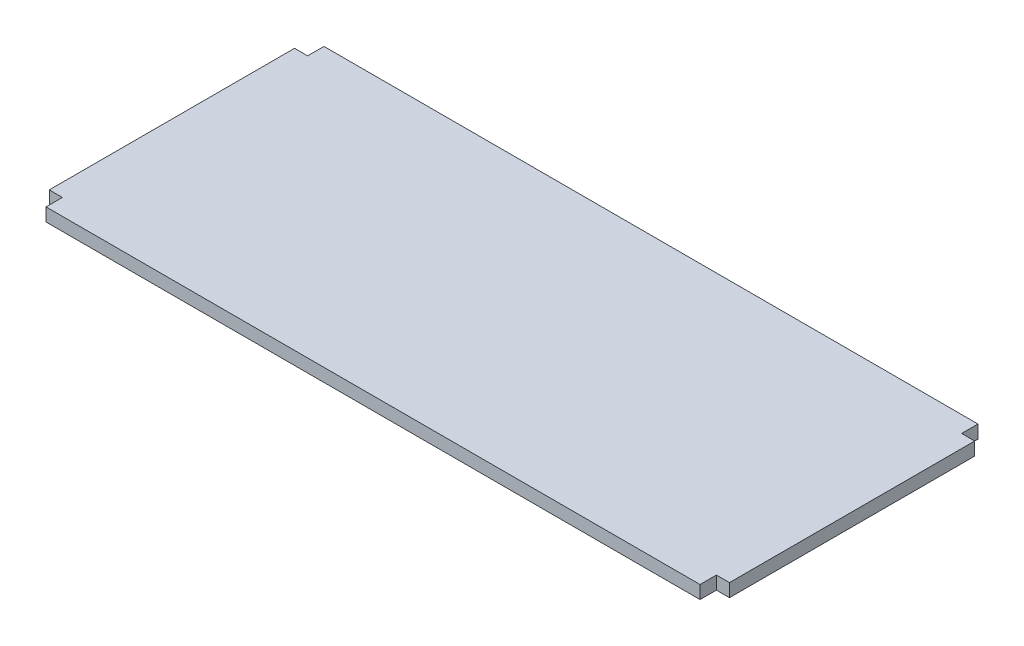
SolidWorks part; units mm, degrees
ref_plane "前视基准面" through (0, 0, 0) normal (0, 0, 1) x (1, 0, 0)
ref_plane "上视基准面" through (0, 0, 0) normal (0, 1, 0) x (1, 0, 0)
ref_plane "右视基准面" through (0, 0, 0) normal (1, 0, 0) x (0, 0, -1)
sketch "草图1" plane through (0, 0, 0) normal (0, 1, 0) x (1, 0, 0)
  line L0 (0, 0) -> (100, 0)
  line L1 (0, 0) -> (0, 42.5)
  line L2 (100, 0) -> (100, 42.5)
  line L3 (0, 42.5) -> (100, 42.5)
  line L4 (-2, 40) -> (0, 40)
  line L5 (-2, 40) -> (-2, 2.5)
  line L6 (0, 40) -> (0, 2.5)
  line L7 (-2, 2.5) -> (0, 2.5)
  line L8 (100, 40) -> (102, 40)
  line L9 (100, 40) -> (100, 2.5)
  line L10 (102, 40) -> (102, 2.5)
  line L11 (100, 2.5) -> (102, 2.5)
  point P0 (0, 40)
  point P3 (0, 2.5)
  point P4 (100, 2.5)
  point P5 (100, 40)
  point P6 (-2, 2.5)
  point P7 (-2, 40)
  point P8 (102, 2.5)
  point P12 (102, 40)
extrude "凸台-拉伸1" add sketch "草图1" along normal blind 2 contours L5 L7 L1 L4 | L3 L1 L0 L2 | L2 L11 L10 L8
